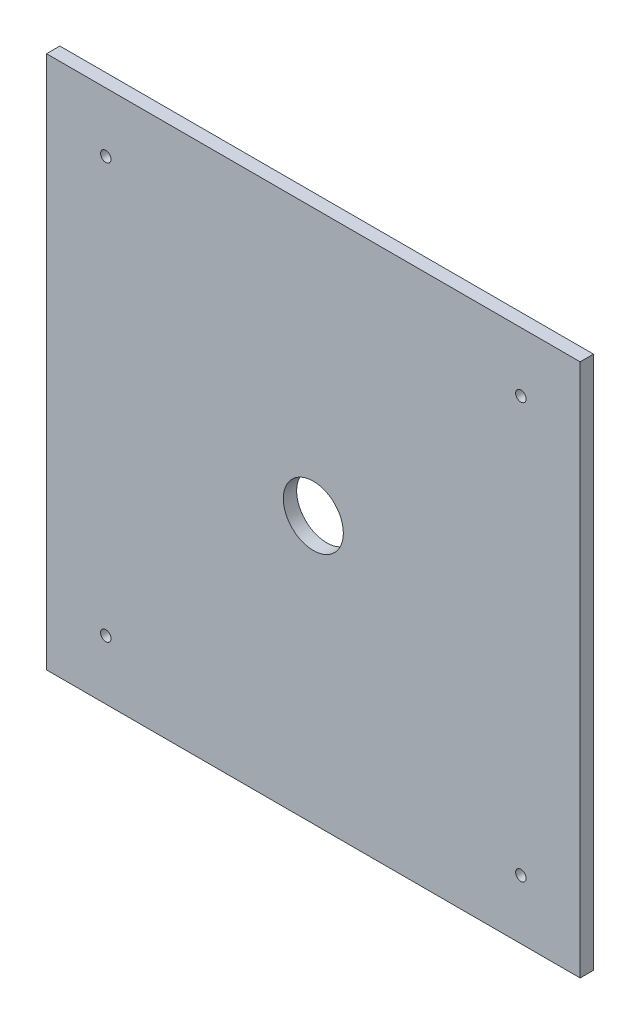
SolidWorks part; units mm, degrees
ref_plane "Front Plane" through (0, 0, 0) normal (0, 0, 1) x (1, 0, 0)
ref_plane "Top Plane" through (0, 0, 0) normal (0, 1, 0) x (1, 0, 0)
ref_plane "Right Plane" through (0, 0, 0) normal (1, 0, 0) x (0, 0, -1)
sketch "Sketch1" plane through (0, 0, 0) normal (0, 0, 1) x (1, 0, 0)
  line L0 (0, 49.5808) -> (0, 0) construction
  line L1 (-41.222, 29.6882) -> (0, 49.5808) construction
  line L2 (0, 63.8683) -> (0, 127) construction
  line L3 (-52.2611, 52.5639) -> (-30.1828, 6.8125) construction
  line L4 (-127, -127) -> (127, -127)
  line L5 (-127, -127) -> (-127, 127)
  line L6 (-127, 127) -> (127, 127)
  line L7 (127, -127) -> (127, 127)
  line L8 (-127, -127) -> (127, 127) construction
  line L9 (-127, 127) -> (127, -127) construction
  line L10 (0, -14.2875) -> (0, -127) construction
  line L11 (-41.222, 29.6882) -> (0, 0) construction
  line L13 (-88.9, 17.8308) -> (88.9, 17.8308) construction
  line L14 (-88.9, 17.8308) -> (-88.9, 81.3308) construction
  line L15 (-88.9, 81.3308) -> (88.9, 81.3308) construction
  line L16 (88.9, 17.8308) -> (88.9, 81.3308) construction
  line L17 (-88.9, 17.8308) -> (88.9, 81.3308) construction
  line L18 (-88.9, 81.3308) -> (88.9, 17.8308) construction
  circle A0 centre (0, 0) radius 114.3 construction
  circle A1 centre (0, 0) radius 38.1 construction
  circle A2 centre (0, 49.5808) radius 11.43 construction
  circle A3 centre (0, 49.5808) radius 38.1 construction
  circle A4 centre (-41.222, 29.6882) radius 7.62 construction
  circle A6 centre (-41.222, 29.6882) radius 10.16
  circle A8 centre (-41.222, 29.6882) radius 25.4 construction
  circle A9 centre (-41.222, 29.6882) radius 33.02 construction
  circle A12 centre (-41.222, 29.6882) radius 8.89 construction
  circle A13 centre (0, 0) radius 39.37 construction
  circle A14 centre (0, 49.5808) radius 14.2875
  circle A15 centre (0, 0) radius 127 construction
  circle A16 centre (-98.7828, 98.7828) radius 12.7 construction
  circle A17 centre (-98.7828, 98.7828) radius 6.35 construction
  circle A18 centre (0, 0) radius 14.2875
  circle A19 centre (-98.7828, -98.7828) radius 12.7 construction
  circle A20 centre (-98.7828, -98.7828) radius 6.35 construction
  circle A21 centre (0, 49.5808) radius 39.37 construction
  circle A22 centre (0, 49.5808) radius 12.7 construction
  circle A23 centre (41.222, 29.6882) radius 10.16
  circle A24 centre (-82.55, 74.9808) radius 6.35 construction
  circle A25 centre (82.55, 74.9808) radius 6.35 construction
  circle A26 centre (82.55, 24.1808) radius 6.35 construction
  circle A27 centre (-82.55, 24.1808) radius 6.35 construction
  point P24 (-41.222, 29.6882)
  point P27 (-98.7828, 98.7828)
  point P32 (-98.7828, -98.7828)
  point P33 (-52.2611, 52.5639)
  point P34 (-30.1828, 6.8125)
  point P40 (52.2611, 52.5639)
  point P41 (30.1828, 6.8125)
  point P42 (98.7828, -98.7828)
  point P43 (98.7828, 98.7828)
  point P59 (82.55, 24.1808)
  point P60 (-82.55, 24.1808)
  point P61 (-82.55, 74.9808)
  point P65 (82.55, 74.9808)
  dimension "D1" = 228.6
  dimension "D2" = 76.2
  dimension "D3" = 22.86
  dimension "D5" = 76.2
  dimension "D6" = 15.24
  dimension "D7" = 28.575
  dimension "D8" = 20.32
  dimension "D9" = 25.4
  dimension "D12" = 66.04
  dimension "D13" = 28.575
  dimension "D14" = 50.8
  dimension "D15" = 25.4
  dimension "D18" = 78.74
  dimension "D19" = 17.78
  dimension "D11" = 12.7
  dimension "D20" = 12.7
  dimension "D21" = 78.74
  dimension "D22" = 25.4
  dimension "D26" = 12.7
  dimension "D27" = 12.7
  dimension "D28" = 12.7
  dimension "D29" = 12.7
  dimension "D4" = 49.5808
  dimension "D10" = 45.7708
  dimension "D16" = 254
  dimension "D17" = 254
  dimension "D23" = 50.8
  dimension "D24" = 177.8
  dimension "D25" = 63.5
extrude "Boss-Extrude2" add sketch "Sketch1" along normal blind 6.35 contours L4 L7 L6 L5 A6 A14 A18 A23 | A14 | A23 | A6
hole_wizard "#9 (0.196) Diameter Hole1" positions "Sketch2" profile "Sketch3" hole size "#9" standard "ANSI Inch"
sketch "Sketch2" plane through (0, 0, 0) normal (0, 0, -1) x (-1, 0, 0)
  point P0 (-98.7828, 98.7828)
  point P3 (98.7828, 98.7828)
  point P6 (98.7828, -98.7828)
  point P9 (-98.7828, -98.7828)
sketch "Sketch3" plane through (98.7828, 98.7828, 0) normal (1, 0, 0) x (0, 1, 0)
  line L0 (0, 0) -> (0, 7.8457)
  line L1 (0, 7.8457) -> (2.4892, 6.35)
  line L2 (2.4892, 6.35) -> (2.4892, 0)
  line L5 (2.4892, 0) -> (0, 0)
  line L10 (0, 7.8457) -> (-2.4892, 6.35) construction
  line L11 (0, -6.35) -> (0, 107.95) construction
  dimension "Hole Dia." = 4.9784
  dimension "Hole Depth" = 6.35
  dimension "Drill Angle" = 118
